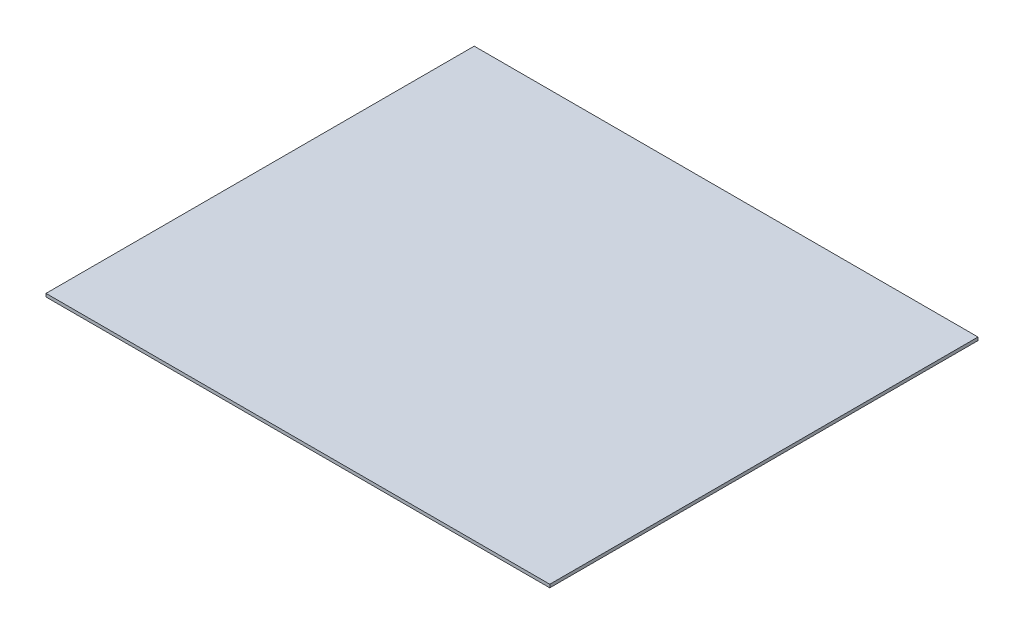
SolidWorks part; units mm, degrees
ref_plane "Front" through (0, 0, 0) normal (0, 0, 1) x (1, 0, 0)
ref_plane "Top" through (0, 0, 0) normal (0, 1, 0) x (1, 0, 0)
ref_plane "Right" through (0, 0, 0) normal (1, 0, 0) x (0, 0, -1)
sketch "Sketch1" plane through (0, 0, 0) normal (0, 1, 0) x (1, 0, 0)
  line L1 (-381, -323.85) -> (381, -323.85)
  line L2 (-381, -323.85) -> (-381, 323.85)
  line L3 (-381, 323.85) -> (381, 323.85)
  line L4 (381, -323.85) -> (381, 323.85)
  line L5 (-381, -323.85) -> (381, 323.85) construction
  line L6 (-381, 323.85) -> (381, -323.85) construction
  point P0 (0, 0)
  dimension "D1" = 762
  dimension "D2" = 647.7
extrude "Boss-Extrude1" add sketch "Sketch1" along normal blind 4.7625
